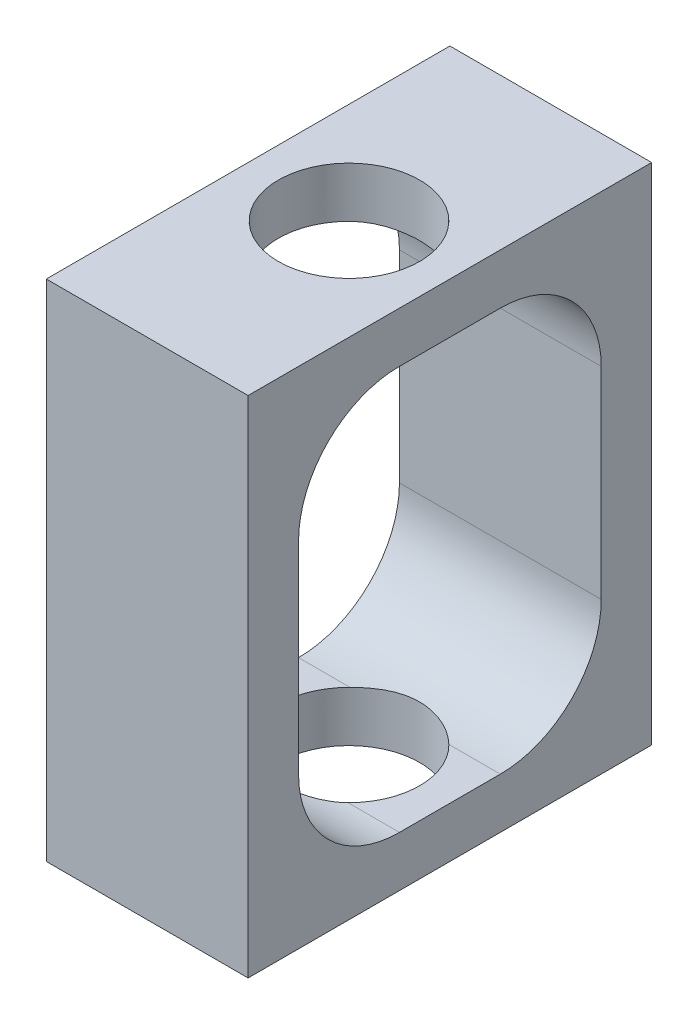
SolidWorks part; units mm, degrees
ref_plane "Front Plane" through (0, 0, 0) normal (0, 0, 1) x (1, 0, 0)
ref_plane "Top Plane" through (0, 0, 0) normal (0, 1, 0) x (1, 0, 0)
ref_plane "Right Plane" through (0, 0, 0) normal (1, 0, 0) x (0, 0, -1)
sketch "Sketch1" plane through (0, 0, 0) normal (1, 0, 0) x (0, 0, -1)
  line L1 (-5, 20) -> (5, 20)
  line L2 (-15, 10) -> (-15, -10)
  line L3 (-5, -20) -> (5, -20)
  line L4 (15, 10) -> (15, -10)
  line L5 (-15, 20) -> (15, -20) construction
  line L6 (-15, -20) -> (15, 20) construction
  line L7 (-20, 25) -> (20, 25)
  line L8 (-20, 25) -> (-20, -25)
  line L9 (-20, -25) -> (20, -25)
  line L10 (20, 25) -> (20, -25)
  line L11 (-20, 25) -> (20, -25) construction
  line L12 (-20, -25) -> (20, 25) construction
  arc A0 (-5, 20) -> (-15, 10) centre (-5, 10) ccw
  arc A1 (5, 20) -> (15, 10) centre (5, 10) cw
  arc A2 (5, -20) -> (15, -10) centre (5, -10) ccw
  arc A3 (-15, -10) -> (-5, -20) centre (-5, -10) ccw
  point P0 (0, 0)
  point P6 (0, 0)
  dimension "D5" = 10
  dimension "D1" = 5
  dimension "D2" = 5
  dimension "D3" = 50
  dimension "D4" = 40
extrude "Boss-Extrude1" add sketch "Sketch1" along normal mid plane 20
sketch "Sketch3" plane through (0, 25, 0) normal (0, 1, 0) x (1, 0, 0)
  circle A0 centre (0, 0) radius 7
  dimension "D1" = 14
extrude "Cut-Extrude1" cut sketch "Sketch3" against normal through all
